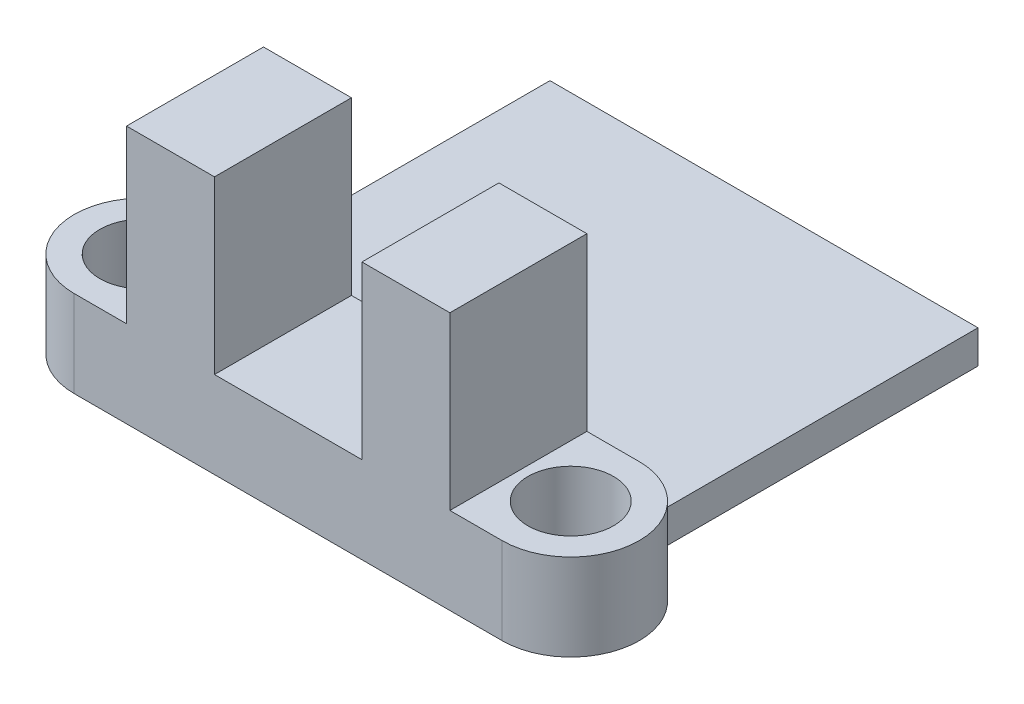
SolidWorks part; units mm, degrees
ref_plane "Front Plane" through (0, 0, 0) normal (0, 0, 1) x (1, 0, 0)
ref_plane "Top Plane" through (0, 0, 0) normal (0, 1, 0) x (1, 0, 0)
ref_plane "Right Plane" through (0, 0, 0) normal (1, 0, 0) x (0, 0, -1)
sketch "Sketch1" plane through (0, 0, 0) normal (0, 1, 0) x (1, 0, 0)
  line L0 (10, -4.715) -> (10, 11.115)
  line L1 (-10, -11.115) -> (10, -11.115)
  line L2 (-10, -4.715) -> (-10, 11.115)
  line L3 (-10, 11.115) -> (10, 11.115)
  line L5 (-10, -11.115) -> (10, 11.115) construction
  line L6 (-10, 11.115) -> (10, -11.115) construction
  arc A0 (-10, -4.715) -> (-10, -11.115) centre (-10, -7.915) ccw
  arc A1 (10, -11.115) -> (10, -4.715) centre (10, -7.915) ccw
  point P0 (0, 0)
  dimension "D3" = 3.2
  dimension "D1" = 20
  dimension "D2" = 22.23
  dimension "D5" = 3.2
extrude "Boss-Extrude1" add sketch "Sketch1" along normal blind 1.55
sketch "Sketch3" plane through (0, 1.55, 0) normal (0, 1, 0) x (1, 0, 0)
  line L1 (-10, -7.915) -> (10, -7.915) construction
  line L2 (-10, -4.715) -> (10, -4.715)
  line L3 (-10, -11.115) -> (10, -11.115)
  arc A2 (-10, -4.715) -> (-10, -11.115) centre (-10, -7.915) ccw
  arc A3 (10, -11.115) -> (10, -4.715) centre (10, -7.915) ccw
  point P10 (0, -7.915)
  dimension "D1" = 3.2
extrude "Boss-Extrude2" add sketch "Sketch3" along normal blind 2.5
sketch "Sketch4" plane through (0, 4.05, 0) normal (0, 1, 0) x (1, 0, 0)
  line L0 (10, -4.715) -> (-10, -4.715) construction
  line L1 (-7.555, -11.115) -> (-3.445, -11.115)
  line L2 (-7.555, -11.115) -> (-7.555, -4.715)
  line L3 (-7.555, -4.715) -> (-3.445, -4.715)
  line L4 (-3.445, -11.115) -> (-3.445, -4.715)
  line L5 (-7.555, -11.115) -> (-3.445, -4.715) construction
  line L6 (-7.555, -4.715) -> (-3.445, -11.115) construction
  line L7 (10, -4.715) -> (-10, -4.715) construction
  line L8 (3.445, -11.115) -> (7.555, -11.115)
  line L9 (3.445, -11.115) -> (3.445, -4.715)
  line L10 (3.445, -4.715) -> (7.555, -4.715)
  line L11 (7.555, -11.115) -> (7.555, -4.715)
  line L12 (3.445, -11.115) -> (7.555, -4.715) construction
  line L13 (3.445, -4.715) -> (7.555, -11.115) construction
  line L14 (-10, 11.115) -> (-10, -4.715) construction
  line L15 (10, -4.715) -> (10, 11.115) construction
  point P0 (-5.5, -7.915)
  point P7 (5.5, -7.915)
  dimension "D1" = 4.5
  dimension "D2" = 4.5
  dimension "D3" = 4.11
  dimension "D4" = 4.11
extrude "Boss-Extrude3" add sketch "Sketch4" along normal blind 8
sketch "Sketch6" plane through (0, 4.05, 0) normal (0, 1, 0) x (1, 0, 0)
  circle A0 centre (-10, -7.915) radius 2
  circle A1 centre (10, -7.915) radius 2
  dimension "D1" = 4
  dimension "D2" = 4
extrude "Cut-Extrude1" cut sketch "Sketch6" against normal through all
